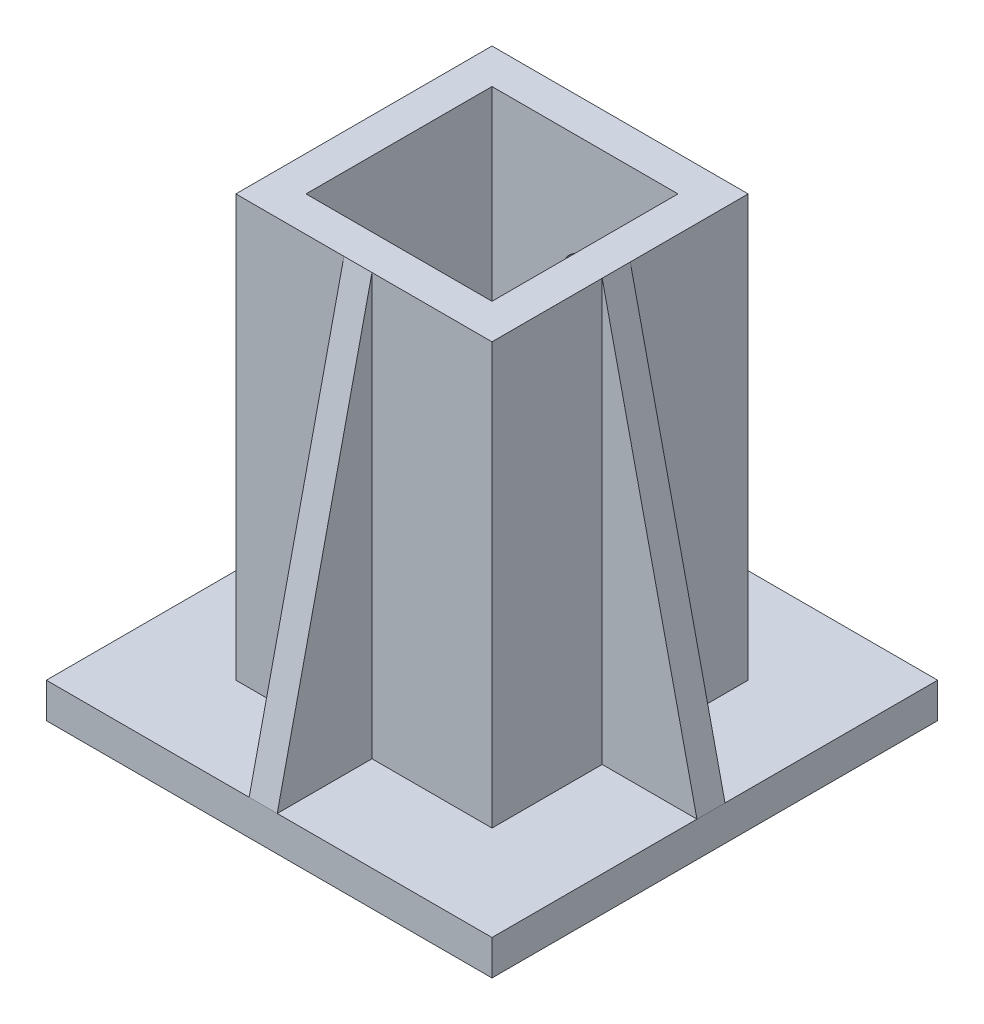
SolidWorks part; units mm, degrees
ref_plane "Front Plane" through (0, 0, 0) normal (0, 0, 1) x (1, 0, 0)
ref_plane "Top Plane" through (0, 0, 0) normal (0, 1, 0) x (1, 0, 0)
ref_plane "Right Plane" through (0, 0, 0) normal (1, 0, 0) x (0, 0, -1)
sketch "Sketch1" plane through (0, 0, 0) normal (0, 1, 0) x (1, 0, 0)
  line L1 (31.75, 31.75) -> (-31.75, 31.75)
  line L2 (31.75, 31.75) -> (31.75, -31.75)
  line L3 (31.75, -31.75) -> (-31.75, -31.75)
  line L4 (-31.75, 31.75) -> (-31.75, -31.75)
  line L5 (31.75, 31.75) -> (-31.75, -31.75) construction
  line L6 (31.75, -31.75) -> (-31.75, 31.75) construction
  point P0 (0, 0)
  dimension "D1" = 63.5
  dimension "D2" = 63.5
extrude "Boss-Extrude1" add sketch "Sketch1" along normal blind 5
sketch "Sketch2" plane through (0, 5, 0) normal (0, 1, 0) x (1, 0, 0)
  line L0 (18.25, 18.25) -> (-18.25, 18.25)
  line L1 (13.25, -13.25) -> (-13.25, -13.25)
  line L2 (13.25, -13.25) -> (13.25, 13.25)
  line L3 (13.25, 13.25) -> (-13.25, 13.25)
  line L4 (-13.25, -13.25) -> (-13.25, 13.25)
  line L5 (13.25, -13.25) -> (-13.25, 13.25) construction
  line L6 (13.25, 13.25) -> (-13.25, -13.25) construction
  line L7 (-18.25, -18.25) -> (-18.25, 18.25)
  line L8 (18.25, -18.25) -> (-18.25, -18.25)
  line L9 (18.25, -18.25) -> (18.25, 18.25)
  point P0 (0, 0)
  dimension "D3" = 5
  dimension "D1" = 26.5
  dimension "D2" = 26.5
extrude "Boss-Extrude2" add sketch "Sketch2" along normal blind 60
ref_plane "Plane2" through (0, 0, 0.55) normal (0, 0, 1) x (1, 0, 0)
sketch "Sketch11" plane through (0, 0, 0.55) normal (0, 0, 1) x (1, 0, 0)
  line L0 (-18.25, 65) -> (-31.75, 5)
sketch "Sketch13" plane through (0, 5, 0) normal (0, 1, 0) x (1, 0, 0)
  line L0 (-31.75, 31.75) -> (-31.75, -31.75) construction
  line L1 (-31.75, 1.45) -> (-18.25, 1.45)
  line L2 (-31.75, 1.45) -> (-31.75, -2.55)
  line L3 (-31.75, -2.55) -> (-18.25, -2.55)
  line L4 (-18.25, 1.45) -> (-18.25, -2.55)
  line L5 (-18.25, 18.25) -> (-18.25, -18.25) construction
  line L6 (-18.25, -0.55) -> (-31.75, -0.55) construction
  dimension "D1" = 2
  dimension "D2" = 2
extrude "Boss-Extrude3" add sketch "Sketch13" along normal blind 60
sketch "Sketch14" plane through (0, 0, 2.55) normal (0, 0, 1) x (1, 0, 0)
  line L0 (-31.75, 5) -> (-18.25, 65)
extrude "Cut-Extrude1" cut sketch "Sketch14" against normal through all and the other way through all contours L0
sketch "Sketch15" plane through (0, 5, 0) normal (0, 1, 0) x (1, 0, 0)
  line L0 (18.25, -18.25) -> (18.25, 18.25) construction
  line L1 (18.25, 1.45) -> (31.75, 1.45)
  line L2 (18.25, 1.45) -> (18.25, -2.55)
  line L3 (18.25, -2.55) -> (31.75, -2.55)
  line L4 (31.75, 1.45) -> (31.75, -2.55)
  line L5 (31.75, -31.75) -> (31.75, 31.75) construction
  line L6 (-8.47, -0.55) -> (8.47, -0.55) construction
  dimension "D1" = 2
  dimension "D2" = 2
extrude "Boss-Extrude4" add sketch "Sketch15" along normal blind 60
sketch "Sketch16" plane through (0, 0, 2.55) normal (0, 0, 1) x (1, 0, 0)
  line L0 (31.75, 5) -> (18.25, 65)
extrude "Cut-Extrude3" cut sketch "Sketch16" against normal through all and the other way through all flip side to cut
sketch "Sketch17" plane through (0, 5, 0) normal (0, 1, 0) x (1, 0, 0)
  line L0 (-18.25, -18.25) -> (18.25, -18.25) construction
  line L1 (-2.85, -18.25) -> (1.15, -18.25)
  line L2 (-2.85, -18.25) -> (-2.85, -31.75)
  line L3 (-2.85, -31.75) -> (1.15, -31.75)
  line L4 (1.15, -18.25) -> (1.15, -31.75)
  line L5 (-31.75, -31.75) -> (31.75, -31.75) construction
  dimension "D1" = 15.4
  dimension "D2" = 4
extrude "Boss-Extrude5" add sketch "Sketch17" along normal blind 60
sketch "Sketch18" plane through (-2.85, 0, 0) normal (-1, 0, 0) x (0, 0, 1)
  line L0 (31.75, 5) -> (18.25, 65)
extrude "Cut-Extrude4" cut sketch "Sketch18" against normal through all and the other way through all flip side to cut
sketch "Sketch21" plane through (0, 0, -18.25) normal (0, 0, -1) x (-1, 0, 0)
  circle A0 centre (0, 17.7394) radius 3.175
  circle A1 centre (0, 47.4664) radius 3.175
  dimension "D1" = 6.35
extrude "Cut-Extrude7" cut sketch "Sketch21" against normal blind 20
